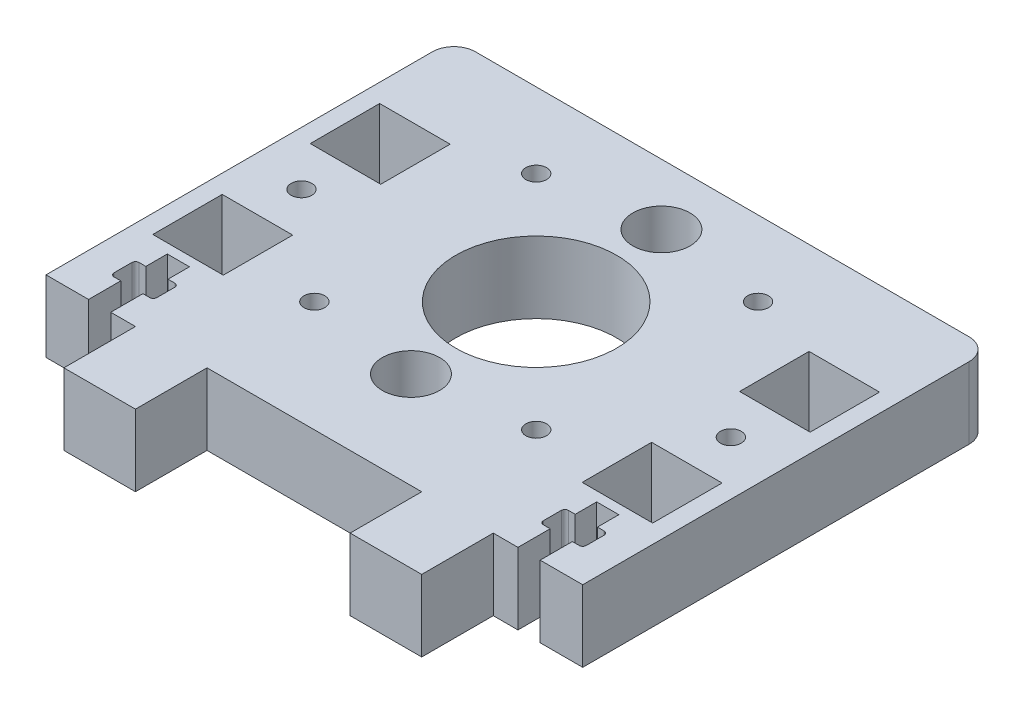
SolidWorks part; units mm, degrees
ref_plane "Front Plane" through (0, 0, 0) normal (0, 0, 1) x (1, 0, 0)
ref_plane "Top Plane" through (0, 0, 0) normal (0, 1, 0) x (1, 0, 0)
ref_plane "Right Plane" through (0, 0, 0) normal (1, 0, 0) x (0, 0, -1)
sketch "Sketch1" plane through (0, 0, 0) normal (0, 1, 0) x (1, 0, 0)
  line L0 (0, 31) -> (0, -8.5) construction
  line L1 (-34.5, 31) -> (0, 31)
  line L2 (-37.5, 28) -> (-37.5, -26)
  line L3 (-37.5, -26) -> (-25, -26)
  line L4 (0, 31) -> (0, 16.25)
  line L5 (0, -6.25) -> (0, -8.5)
  line L6 (0, -16.5) -> (0, -26) construction
  line L7 (-11.25, 5) -> (0, 5) construction
  line L8 (0, -16.5) -> (0, -26)
  line L9 (-30, 18.05) -> (-30, 8.35) construction
  line L10 (-37.5, 2.2) -> (0, 2.2) construction
  line L11 (-34.925, 18.05) -> (-25.075, 18.05)
  line L12 (-34.925, 18.05) -> (-34.925, 8.35)
  line L13 (-34.925, 8.35) -> (-25.075, 8.35)
  line L14 (-25.075, 18.05) -> (-25.075, 8.35)
  line L15 (-34.925, 18.05) -> (-25.075, 8.35) construction
  line L16 (-34.925, 8.35) -> (-25.075, 18.05) construction
  line L17 (-34.925, -3.95) -> (-25.075, -13.65) construction
  line L18 (-34.925, -13.65) -> (-25.075, -3.95) construction
  line L19 (-25.075, -13.65) -> (-25.075, -3.95)
  line L20 (-34.925, -3.95) -> (-25.075, -3.95)
  line L21 (-34.925, -13.65) -> (-34.925, -3.95)
  line L22 (-34.925, -13.65) -> (-25.075, -13.65)
  line L23 (-30, -3.95) -> (-30, -13.65) construction
  line L24 (-30, -8.8) -> (-30, 13.2) construction
  line L25 (0, 5) -> (-15.5, 20.5) construction
  line L35 (-15, -26) -> (0, -26)
  line L43 (-20, -36) -> (-20, -24.65) construction
  line L44 (-15, -26) -> (-15, -36)
  line L45 (-15, -36) -> (-25, -36)
  line L46 (-25, -36) -> (-25, -26)
  arc A1 (-34.5, 31) -> (-37.5, 28) centre (-34.5, 28) ccw
  arc A2 (0, 16.25) -> (0, -6.25) centre (0, 5) ccw
  circle A4 centre (-15.5, 20.5) radius 1.45
  circle A6 centre (-15.5, -10.5) radius 1.45
  circle A7 centre (-30, 2.2) radius 1.45
  arc A10 (0, -8.5) -> (0, -16.5) centre (0, -12.5) ccw
  point P0 (0, 0)
  point P28 (-30, 13.2)
  point P39 (-30, -8.8)
  dimension "D7" = 22.5
  dimension "D17" = 8
  dimension "D14" = 2.9
  dimension "D6" = 3
  dimension "D19" = 2.9
  dimension "D1" = 57
  dimension "D9" = 9.85
  dimension "D10" = 9.7
  dimension "D22" = 10
  dimension "D23" = 10
  dimension "D16" = 17.5
  dimension "D11" = 22
  dimension "D13" = 2.2
  dimension "D3" = 37.5
  dimension "D4" = 31
  dimension "D5" = 15.5
  dimension "D15" = 26
  dimension "D18" = 37.5
  dimension "D20" = 20
  dimension "D8" = 13.5
  dimension "D12" = 30
extrude "MainLayout" add sketch "Sketch1" along normal blind 10
sketch "Sketch2" plane through (0, 10, 0) normal (0, 1, 0) x (1, 0, 0)
  line L0 (-30, -26) -> (-30, -15) construction
  line L1 (-28.45, -21.5) -> (-28.45, -26)
  line L2 (-37.5, -26) -> (-25, -26) construction
  line L3 (-28.45, -15) -> (-31.55, -15)
  line L4 (-31.55, -15) -> (-31.55, -18)
  line L5 (-31.55, -18) -> (-32.5, -18)
  line L6 (-33, -18.5) -> (-33, -21)
  line L7 (-32.5, -21.5) -> (-31.55, -21.5)
  line L8 (-31.55, -21.5) -> (-31.55, -26)
  line L9 (-31.55, -26) -> (-28.45, -26)
  line L10 (-27.5, -21.5) -> (-28.45, -21.5)
  line L11 (-27, -18.5) -> (-27, -21)
  line L12 (-28.45, -18) -> (-27.5, -18)
  line L13 (-28.45, -15) -> (-28.45, -18)
  line L14 (0, -26) -> (0, -16.5) construction
  line L30 (-30, -26) -> (-30, -15) construction
  arc A0 (-27, -18.5) -> (-27.5, -18) centre (-27.5, -18.5) ccw
  arc A1 (-32.5, -18) -> (-33, -18.5) centre (-32.5, -18.5) ccw
  arc A2 (-27.5, -21.5) -> (-27, -21) centre (-27.5, -21) ccw
  arc A3 (-33, -21) -> (-32.5, -21.5) centre (-32.5, -21) ccw
  point P17 (0, -21.25)
  point P38 (-27, -18)
  point P41 (-33, -18)
  point P44 (-27, -21.5)
  point P47 (-33, -21.5)
  dimension "D8" = 0.5
  dimension "D1" = 1.55
  dimension "D2" = 0
  dimension "D3" = 3.5
  dimension "D5" = 11
  dimension "D6" = 3
  dimension "D4" = 8
  dimension "D7" = 30
extrude "TSlot" cut sketch "Sketch2" against normal through all
mirror "Mirror1" about plane through (0, 0, 0) normal (1, 0, 0) of "TSlot", "MainLayout"
sketch "Sketch3" plane through (0, 10, 0) normal (0, 1, 0) x (1, 0, 0)
  line L0 (0, 31) -> (0, 0) construction
  line L1 (34.5, 31) -> (-34.5, 31) construction
  line L2 (-11.25, 5) -> (11.25, 5) construction
  circle A0 centre (0, 22.5) radius 4
  circle A1 centre (0, -12.5) radius 4 construction
  circle A2 centre (0, 5) radius 11.25 construction
  dimension "D1" = 17.5
extrude "Cut-Extrude1" cut sketch "Sketch3" against normal through all
equation "\"Y-ROD-SPACING\"=75"
equation "\"Y-BED-OFFSET\"=2"
equation "\"Y-BED-ROD-INSET\"=3.5"
equation "\"T-SLOT-NUT-FILLET-RADIUS\"=0.5"
equation "\"T-SLOT-SCREW-SHAFT-RADIUS\"=1.55"
equation "\"T-SLOT-SCREW-SHAFT-CUTOUT-LENGTH\"=11"
equation "\"T-SLOT-NUT-DEPTH\"=3.5"
equation "\"T-SLOT-NUT-WIDTH\"=2.85"
equation "\"T-SLOT-NUT-END-DISTANCE\"=8"
equation "\"ACRYLIC-TAB-CUTOUT-SIZE\"=\"ACRYLIC-THICKNESS\"+\"ACRYLIC-TAB-TOLERANCE\"*2"
equation "\"ACRYLIC-TAB-WIDTH\"=\"ACRYLIC-THICKNESS\""
equation "\"ACRYLIC-M3-HOLE\"=2.9"
equation "\"SMOOTHROD-CAP-SCREW-DISTANCE\"=20"
equation "\"FRAME-WIDTH-INNER\"=370"
equation "\"NEMA17-HOLE-SPACING\"=31"
equation "\"NEMA17-CENTRAL-CUTOUT\"=22.5"
equation "\"D7@Sketch1\"=\"NEMA17-CENTRAL-CUTOUT\""
equation "\"D5@Sketch1\"=\"NEMA17-HOLE-SPACING\"/2"
equation "\"D4@Sketch1\"=\"NEMA17-HOLE-SPACING\""
equation "\"D19@Sketch1\"=\"ACRYLIC-M3-HOLE\""
equation "\"D14@Sketch1\"=\"ACRYLIC-M3-HOLE\""
equation "\"D9@Sketch1\"=\"ACRYLIC-THICKNESS\"-\"KERF\"*2"
equation "\"D10@Sketch1\"=\"ACRYLIC-TAB-WIDTH\"-\"KERF\"*4"
equation "\"D23@Sketch1\"=\"ACRYLIC-TAB-WIDTH\""
equation "\"D22@Sketch1\"=\"ACRYLIC-TAB-WIDTH\""
equation "\"D5@Sketch2\"=\"T-SLOT-SCREW-SHAFT-CUTOUT-LENGTH\""
equation "\"D4@Sketch2\"=\"T-SLOT-NUT-END-DISTANCE\""
equation "\"D3@Sketch2\"=\"T-SLOT-NUT-DEPTH\""
equation "\"D1@Sketch2\"=\"T-SLOT-SCREW-SHAFT-RADIUS\""
equation "\"D8@Sketch2\"=\"T-SLOT-NUT-FILLET-RADIUS\""
equation "\"Z-BRACKET-REACH\"=57"
equation "\"D1@Sketch1\"=\"Z-BRACKET-REACH\""
equation "\"Z-ROD-SPACING\"=17.5"
equation "\"ACRYLIC-THICKNESS\"=10"
equation "\"TOP-BRACKET-SPACING\"=40"
equation "\"SMOOTHROD-X-LENGTH\"=350"
equation "\"SMOOTHROD-Y-LENGTH\"=350"
equation "\"SMOOTHROD-Z-LENGTH\"=350"
equation "\"SMOOTHROD-TIGHTENING-HEADROOM\"=.25"
equation "\"LEADSCREW-Z-LENGTH\"=300"
equation "\"D16@Sketch1\"=\"Z-ROD-SPACING\""
equation "\"X-ROD-SPACING\"=45"
equation "\"ACRYLIC-THICKNESS2\"=4.5"
equation "\"SCREW-LENGTH-FRAME\"=\"ACRYLIC-THICKNESS\" + 10"
equation "\"SCREW-HEAD-RADIUS\"=6"
equation "\"PRINTED-X-SMOOTHROD-DIAMETER\"=8.8"
equation "\"PRINTED-X-SMOOTHROD-CUTOUT\"=10"
equation "\"PRINTED-X-BASE-HEIGHT\"=10"
equation "\"PRINTED-LM8UU-CUTOUT-SIZE\"=15.5"
equation "\"PRINTED-LM8UU-CUTOUT-LENGTH\"=24.5"
equation "\"PRINTED-X-IDLER-HEIGHT\"=16"
equation "\"PSU-MOUNTING-WIDTH\"=95"
equation "\"PSU-MOUNTING-HEIGHT\"=177"
equation "\"D1@MainLayout\"=\"ACRYLIC-THICKNESS\""
equation "\"Z-ROD-INSET\"=13.5"
equation "\"Y-BELT-TO-ROD-DISTANCE\"=20"
equation "\"SPOOL-HOLDER-ROD-SPACING\"=150"
equation "\"D8@Sketch1\"=\"Z-ROD-INSET\""
equation "\"Y-BED-SCREW-SPACING\"=209"
equation "\"Y-BED-SCREW-CUTOUT-SLOT-HEIGHT\"=2.5"
equation "\"ACRYLIC-TAB-TOLERANCE\"=-.05"
equation "\"SCREW-LENGTH-MOTOR\"=\"ACRYLIC-THICKNESS\" + 5"
equation "\"SCREW-LENGTH-EXTRUDER\"=28"
equation "\"ACRYLIC-X-CARRIAGE-WIDTH\"=55"
equation "\"ACRYLIC-X-CARRIAGE-HEIGHT\"=75"
equation "\"ACRYLIC-X-CARRIAGE-LM8UU-CUTOUT-WIDTH\"=24.25"
equation "\"ACRYLIC-X-CARRIAGE-SCREW-SPACING-X\"=15"
equation "\"ACRYLIC-X-CARRIAGE-SCREW-SPACING-Y\"=33"
equation "\"ACRYLIC-X-CARRIAGE-CENTER-TAB-SPACING\"=14"
equation "\"ACRYLIC-X-CARRIAGE-EXTRUDER-OFFSET\"=26"
equation "\"ACRYLIC-X-CARRIAGE-EXTRUDER-ANGLE\"=90"
equation "\"ACRYLIC-X-CARRIAGE-EXTRUDER-SHELF-DEPTH\"=\"ACRYLIC-X-CARRIAGE-EXTRUDER-OFFSET\" + 28"
equation "\"ACRYLIC-X-CARRIAGE-EXTRUDER-BRACE-SPACING\"=23"
equation "\"ACRYLIC-X-CARRIAGE-EXTRUDER-BRACE-TAB-OFFSET\"=20"
equation "\"ACRYLIC-X-CARRIAGE-EXTRUDER-BRACE-HEIGHT\"=35"
equation "\"ACRYLIC-X-CARRIAGE-EXTRUDER-BRACE-SCREW-SPACING\"=22"
equation "\"KERF\"=0.075"
equation "\"PRINTED-M3-HOLE\"=3.5"
equation "\"PRINTED-M3-NUT-AF\"=6.25"
equation "\"ACRYLIC-X-CARRIAGE-LM8UU-CUTOUT-HEIGHT\"=11.0"
equation "\"ACRYLIC-X-CARRIAGE-DUAL-WIDTH-MULTIPLIER\"=1.65"
equation "\"ACRYLIC-X-CARRIAGE-DUAL-HOTEND-SPACING\"=42"
equation "\"ACRYLIC-X-CARRIAGE-DUAL-WIDTH\"=75"
equation "\"ACRYLIC-X-CARRIAGE-DUAL-FAN-OFFSET\"=52"
equation "\"ACRYLIC-X-CARRIAGE-DUAL-FAN-HEIGHT\"=20"
equation "\"ACRYLIC-X-CARRIAGE-DUAL-HOTEND-SEPARATION\"=36"
equation "\"ACRYLIC-X-CARRIAGE-DUAL-MOUNT-PLATE-DEPTH\"=75"
equation "\"ACRYLIC-X-CARRIAGE-DUAL-MOUNT-BRACE-WIDTH\"=33"
equation "\"ACRYLIC-X-CARRIAGE-DUAL-MOUNT-SCREW-WIDTH\"=40"
equation "\"BLOWER-FAN-WIDTH\"=15"
equation "\"D1@Sketch3\"=\"Z-ROD-SPACING\""
